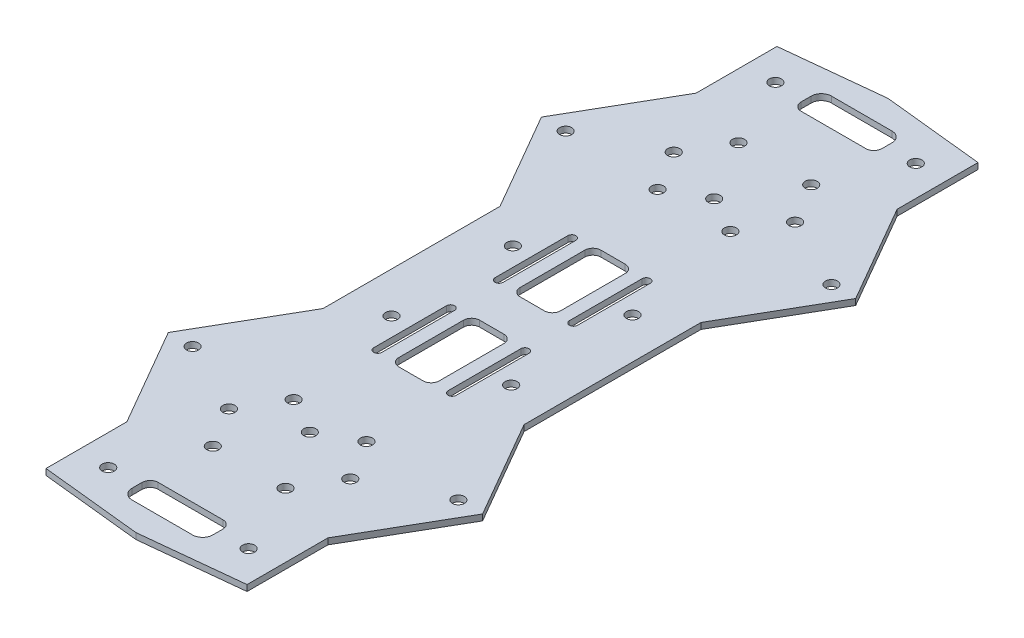
SolidWorks part; units mm, degrees
other "TopFrame"
ref_plane "Front Plane" through (0, 0, 0) normal (0, 0, 1) x (1, 0, 0)
ref_plane "Top Plane" through (0, 0, 0) normal (0, 1, 0) x (1, 0, 0)
ref_plane "Right Plane" through (0, 0, 0) normal (1, 0, 0) x (0, 0, -1)
sketch "Sketch1" plane through (0, 0, 0) normal (0, 1, 0) x (1, 0, 0)
  line L0 (-9.2, 6) -> (-9.2, 24) construction
  line L1 (-3, 5) -> (3, 5)
  line L2 (-5, 7) -> (-5, 23)
  line L3 (-3, 25) -> (3, 25)
  line L4 (5, 7) -> (5, 23)
  line L5 (-5, 5) -> (5, 25) construction
  line L6 (-5, 25) -> (5, 5) construction
  line L11 (-10.2, 6) -> (-10.2, 24)
  line L12 (-8.2, 6) -> (-8.2, 24)
  line L13 (0, 5) -> (0, 25) construction
  line L14 (9.2, 6) -> (9.2, 24) construction
  line L15 (10.2, 6) -> (10.2, 24)
  line L16 (8.2, 6) -> (8.2, 24)
  line L17 (-3, 0) -> (3, 0) construction
  line L18 (0, -5) -> (0, -25) construction
  line L19 (-5, -25) -> (5, -5) construction
  line L20 (-5, -5) -> (5, -25) construction
  line L21 (5, -7) -> (5, -23)
  line L22 (-3, -25) -> (3, -25)
  line L23 (-5, -7) -> (-5, -23)
  line L24 (-3, -5) -> (3, -5)
  line L25 (9.2, -6) -> (9.2, -24) construction
  line L26 (10.2, -6) -> (10.2, -24)
  line L27 (8.2, -6) -> (8.2, -24)
  line L28 (-9.2, -6) -> (-9.2, -24) construction
  line L29 (-10.2, -6) -> (-10.2, -24)
  line L30 (-8.2, -6) -> (-8.2, -24)
  line L31 (0, 93) -> (-24.863, 90.3868)
  line L32 (-24.863, 90.3868) -> (-24.863, 70.3868)
  line L33 (-24.863, 70.3868) -> (-38.863, 46.1381)
  line L34 (-38.863, 46.1381) -> (-24.863, 21.8894)
  line L35 (-24.863, 21.8894) -> (-24.863, -21.8894)
  line L36 (24.863, 21.8894) -> (24.863, -21.8894)
  line L37 (38.863, 46.1381) -> (24.863, 21.8894)
  line L38 (24.863, 70.3868) -> (38.863, 46.1381)
  line L39 (24.863, 90.3868) -> (24.863, 70.3868)
  line L40 (0, 93) -> (24.863, 90.3868)
  line L41 (0, -93) -> (24.863, -90.3868)
  line L42 (24.863, -90.3868) -> (24.863, -70.3868)
  line L43 (24.863, -70.3868) -> (38.863, -46.1381)
  line L44 (38.863, -46.1381) -> (24.863, -21.8894)
  line L45 (-38.863, -46.1381) -> (-24.863, -21.8894)
  line L46 (-24.863, -70.3868) -> (-38.863, -46.1381)
  line L47 (-24.863, -90.3868) -> (-24.863, -70.3868)
  line L48 (0, -93) -> (-24.863, -90.3868)
  arc A0 (-3, 5) -> (-5, 7) centre (-3, 7) cw
  arc A1 (3, 5) -> (5, 7) centre (3, 7) ccw
  arc A2 (3, 25) -> (5, 23) centre (3, 23) cw
  arc A3 (-5, 23) -> (-3, 25) centre (-3, 23) cw
  arc A4 (-10.2, 6) -> (-8.2, 6) centre (-9.2, 6) ccw
  arc A5 (-8.2, 24) -> (-10.2, 24) centre (-9.2, 24) ccw
  arc A6 (10.2, 6) -> (8.2, 6) centre (9.2, 6) cw
  arc A7 (8.2, 24) -> (10.2, 24) centre (9.2, 24) cw
  arc A8 (-5, -23) -> (-3, -25) centre (-3, -23) ccw
  arc A9 (3, -25) -> (5, -23) centre (3, -23) ccw
  arc A10 (3, -5) -> (5, -7) centre (3, -7) cw
  arc A11 (-3, -5) -> (-5, -7) centre (-3, -7) ccw
  arc A12 (10.2, -6) -> (8.2, -6) centre (9.2, -6) ccw
  arc A13 (8.2, -24) -> (10.2, -24) centre (9.2, -24) ccw
  arc A14 (-10.2, -6) -> (-8.2, -6) centre (-9.2, -6) cw
  arc A15 (-8.2, -24) -> (-10.2, -24) centre (-9.2, -24) cw
  circle A16 centre (0, 50) radius 1.5
  circle A17 centre (-9, 45) radius 1.5
  circle A18 centre (-15, 55) radius 1.5
  circle A19 centre (-9, 65) radius 1.5
  circle A20 centre (9, 45) radius 1.5
  circle A21 centre (9, 65) radius 1.5
  circle A22 centre (15, 55) radius 1.5
  circle A23 centre (-14.8, 15) radius 1.5
  circle A24 centre (14.8, 15) radius 1.5
  circle A25 centre (-32.863, 46.1381) radius 1.5
  circle A26 centre (-17.363, 82.5) radius 1.5
  circle A27 centre (32.863, 46.1381) radius 1.5
  circle A28 centre (17.363, 82.5) radius 1.5
  circle A29 centre (-14.8, -15) radius 1.5
  circle A30 centre (14.8, -15) radius 1.5
  circle A31 centre (32.863, -46.1381) radius 1.5
  circle A32 centre (9, -45) radius 1.5
  circle A33 centre (-32.863, -46.1381) radius 1.5
  circle A34 centre (-9, -45) radius 1.5
  circle A35 centre (15, -55) radius 1.5
  circle A36 centre (0, -50) radius 1.5
  circle A37 centre (-15, -55) radius 1.5
  circle A38 centre (-9, -65) radius 1.5
  circle A39 centre (9, -65) radius 1.5
  circle A40 centre (17.363, -82.5) radius 1.5
  circle A41 centre (-17.363, -82.5) radius 1.5
  point P0 (0, 15)
  point P19 (-9.2, 15)
  point P25 (-9.2, 25)
  point P26 (-9.2, 5)
  point P31 (9.2, 15)
  point P58 (9.2, -15)
  point P65 (-9.2, -15)
  point P70 (0, -15)
  point P83 (24.863, 0)
  point P84 (-24.863, 0)
  dimension "D4" = 2
  dimension "D6" = 1
  dimension "D15" = 3
  dimension "D16" = 25
  dimension "D17" = 20
  dimension "D18" = 9
  dimension "D19" = 10
  dimension "D21" = 10
  dimension "D23" = 3
  dimension "D24" = 3
  dimension "D25" = 3
  dimension "D26" = 4.6
  dimension "D27" = 3
  dimension "D28" = 6
  dimension "D29" = 3
  dimension "D30" = 7.5
  dimension "D31" = 3
  dimension "D32" = 57.5
  dimension "D1" = 10
  dimension "D2" = 20
  dimension "D3" = 5
  dimension "D5" = 20
  dimension "D7" = 3.2
  dimension "D8" = 25
  dimension "D9" = 68
  dimension "D10" = 20
  dimension "D11" = 96
  dimension "D12" = 28
  dimension "D13" = 150
  dimension "D14" = 120
  dimension "D20" = 6
  dimension "D22" = 6
extrude "Boss-Extrude1" add sketch "Sketch1" along normal blind 1.5
sketch "Sketch2" plane through (0, 1.5, 0) normal (0, 1, 0) x (1, 0, 0)
  line L0 (0, 0) -> (9, 0) construction
  line L1 (-8, 79.5) -> (8, 79.5)
  line L2 (-10, 81.5) -> (-10, 84)
  line L3 (-7.5, 86.5) -> (7.5, 86.5)
  line L4 (10, 81.5) -> (10, 84)
  line L5 (-10, 79.5) -> (10, 86.5) construction
  line L6 (-10, 86.5) -> (10, 79.5) construction
  line L7 (-10, -86.5) -> (10, -79.5) construction
  line L8 (-10, -79.5) -> (10, -86.5) construction
  line L9 (10, -81.5) -> (10, -84)
  line L10 (-7.5, -86.5) -> (7.5, -86.5)
  line L11 (-10, -81.5) -> (-10, -84)
  line L12 (-8, -79.5) -> (8, -79.5)
  arc A0 (8, 79.5) -> (10, 81.5) centre (8, 81.5) ccw
  arc A1 (-8, 79.5) -> (-10, 81.5) centre (-8, 81.5) cw
  arc A2 (7.5, 86.5) -> (10, 84) centre (7.5, 84) cw
  arc A3 (-10, 84) -> (-7.5, 86.5) centre (-7.5, 84) cw
  arc A4 (-10, -84) -> (-7.5, -86.5) centre (-7.5, -84) ccw
  arc A5 (7.5, -86.5) -> (10, -84) centre (7.5, -84) ccw
  arc A6 (-8, -79.5) -> (-10, -81.5) centre (-8, -81.5) ccw
  arc A7 (8, -79.5) -> (10, -81.5) centre (8, -81.5) cw
  point P0 (0, 83)
  point P36 (0, -83)
  dimension "D3" = 2
  dimension "D5" = 2.5
  dimension "D1" = 20
  dimension "D2" = 7
  dimension "D4" = 79.5
extrude "Cut-Extrude1" cut sketch "Sketch2" against normal up to surface (1.5 mm away) up to face at (17.363, 0, 84)
